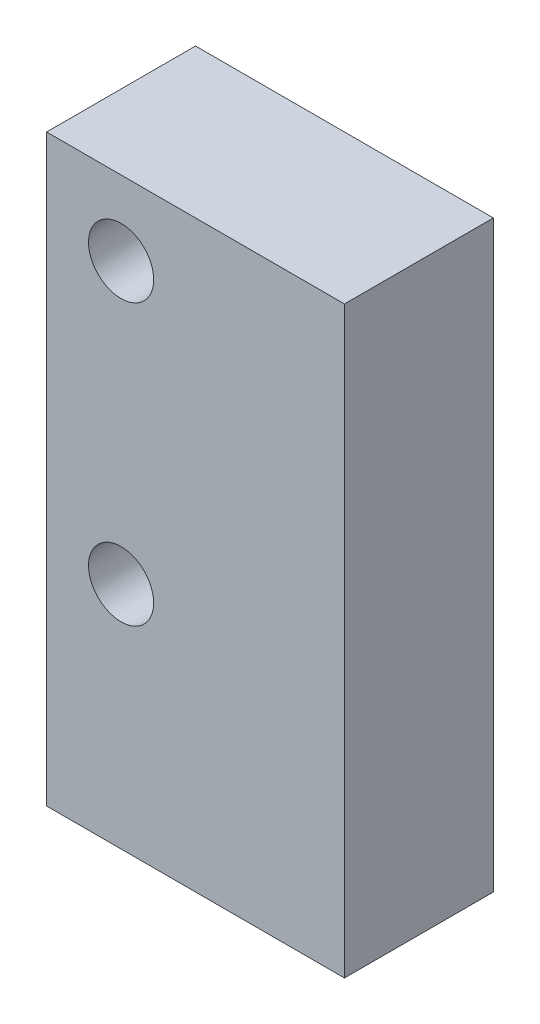
SolidWorks part; units mm, degrees
ref_plane "Front Plane" through (0, 0, 0) normal (0, 0, 1) x (1, 0, 0)
ref_plane "Top Plane" through (0, 0, 0) normal (0, 1, 0) x (1, 0, 0)
ref_plane "Right Plane" through (0, 0, 0) normal (1, 0, 0) x (0, 0, -1)
sketch "Sketch1" plane through (0, 0, 0) normal (0, 0, 1) x (1, 0, 0)
  line B0 (-13.35, 0) -> (0, 0)
  line B1 (0, 0) -> (0, 6.8)
  line B2 (0, 6.8) -> (-6.35, 6.8)
  line B3 (-6.35, 6.8) -> (-6.35, 25)
  line B4 (-6.35, 25) -> (-13.35, 25)
  line B5 (-13.35, 25) -> (-13.35, 0)
sketch_block_instance "Limit_Switch_IC-1"
sketch_block "Limit_Switch_IC"
extrude "Boss-Extrude1" [suppressed] add sketch "Sketch1" along normal blind 6.35
sketch "Sketch2" plane through (0, 0, 0) normal (0, 0, 1) x (1, 0, 0)
  line L0 (3.175, 21.717) -> (3.175, 9.779) construction
  line L1 (0, 0) -> (12.7, 0)
  line L2 (0, 0) -> (0, 24.892)
  line L3 (0, 24.892) -> (12.7, 24.892)
  line L4 (12.7, 0) -> (12.7, 24.892)
  circle A0 centre (3.175, 9.779) radius 1.3891
  circle A1 centre (3.175, 21.717) radius 1.3891
  dimension "D1" = 2.7781
  dimension "D2" = 11.938
  dimension "D3" = 24.892
  dimension "D4" = 3.175
  dimension "D5" = 12.7
  dimension "D6" = 15.113
extrude "Boss-Extrude2" add sketch "Sketch2" along normal blind 6.35
